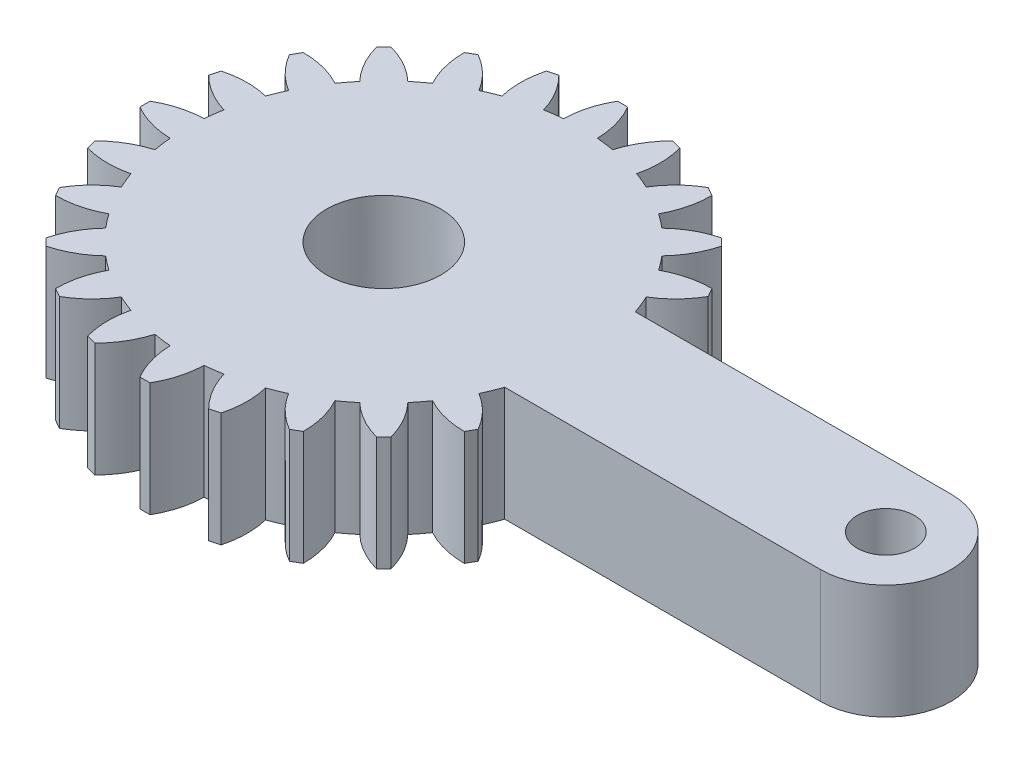
SolidWorks part; units mm, degrees
material "PLA"
ref_plane "Front Plane" through (0, 0, 0) normal (0, 0, 1) x (1, 0, 0)
ref_plane "Top Plane" through (0, 0, 0) normal (0, 1, 0) x (1, 0, 0)
ref_plane "Right Plane" through (0, 0, 0) normal (1, 0, 0) x (0, 0, -1)
sketch "Sketch1" plane through (0, 0, 0) normal (0, 1, 0) x (1, 0, 0)
  line L0 (0, 0) -> (0, 14.63) construction
  line L1 (0, 0) -> (30.75, 0) construction
  line L2 (0.31, 14.63) -> (-0.31, 14.63)
  line L3 (30.75, 4) -> (11.4091, 4)
  line L4 (30.75, -4) -> (11.4091, -4)
  line L5 (4.086, 14.0513) -> (3.4871, 14.2117)
  line L6 (7.5835, 12.515) -> (7.0465, 12.825)
  line L7 (10.5642, 10.1258) -> (10.1258, 10.5642)
  line L8 (12.825, 7.0465) -> (12.515, 7.5835)
  line L9 (14.2117, 3.4871) -> (14.0513, 4.086)
  line L10 (14.63, -0.31) -> (14.63, 0.31)
  line L11 (14.0513, -4.086) -> (14.2117, -3.4871)
  line L12 (12.515, -7.5835) -> (12.825, -7.0465)
  line L13 (10.1258, -10.5642) -> (10.5642, -10.1258)
  line L14 (7.0465, -12.825) -> (7.5835, -12.515)
  line L15 (3.4871, -14.2117) -> (4.086, -14.0513)
  line L16 (-0.31, -14.63) -> (0.31, -14.63)
  line L17 (-4.086, -14.0513) -> (-3.4871, -14.2117)
  line L18 (-7.5835, -12.515) -> (-7.0465, -12.825)
  line L19 (-10.5642, -10.1258) -> (-10.1258, -10.5642)
  line L20 (-12.825, -7.0465) -> (-12.515, -7.5835)
  line L21 (-14.2117, -3.4871) -> (-14.0513, -4.086)
  line L22 (-14.63, 0.31) -> (-14.63, -0.31)
  line L23 (-14.0513, 4.086) -> (-14.2117, 3.4871)
  line L24 (-12.515, 7.5835) -> (-12.825, 7.0465)
  line L25 (-10.1258, 10.5642) -> (-10.5642, 10.1258)
  line L26 (-7.0465, 12.825) -> (-7.5835, 12.515)
  line L27 (-3.4871, 14.2117) -> (-4.086, 14.0513)
  circle A3 centre (0, 0) radius 12.09
  circle A4 centre (0, 0) radius 3.5
  arc A5 (30.75, -4) -> (30.75, 4) centre (30.75, 0) ccw
  arc A6 (-0.31, 14.63) -> (-1.04, 12.0452) centre (4.3585, 11.9161) ccw
  circle A7 centre (30.75, 0) radius 1.75
  arc A8 (0.31, 14.63) -> (1.04, 12.0452) centre (-4.3585, 11.9161) cw
  arc A9 (3.4871, 14.2117) -> (2.113, 11.9039) centre (7.294, 10.382) ccw
  arc A10 (4.086, 14.0513) -> (4.1221, 11.3656) centre (-1.1258, 12.6381) cw
  circle A11 centre (0, 0) radius 12.09
  arc A12 (7.0465, 12.825) -> (5.1219, 10.9514) centre (9.7326, 8.1404) ccw
  arc A13 (7.5835, 12.515) -> (6.9233, 9.9114) centre (2.1835, 12.4988) cw
  circle A14 centre (0, 0) radius 12.09
  arc A15 (10.1258, 10.5642) -> (7.7818, 9.2526) centre (11.5078, 5.344) ccw
  arc A16 (10.5642, 10.1258) -> (9.2526, 7.7818) centre (5.344, 11.5078) cw
  circle A17 centre (0, 0) radius 12.09
  arc A18 (12.515, 7.5835) -> (9.9114, 6.9233) centre (12.4988, 2.1835) ccw
  arc A19 (12.825, 7.0465) -> (10.9514, 5.1219) centre (8.1404, 9.7326) cw
  circle A20 centre (0, 0) radius 12.09
  arc A21 (14.0513, 4.086) -> (11.3656, 4.1221) centre (12.6381, -1.1258) ccw
  arc A22 (14.2117, 3.4871) -> (11.9039, 2.113) centre (10.382, 7.294) cw
  circle A23 centre (0, 0) radius 12.09
  arc A24 (14.63, 0.31) -> (12.0452, 1.04) centre (11.9161, -4.3585) ccw
  arc A25 (14.63, -0.31) -> (12.0452, -1.04) centre (11.9161, 4.3585) cw
  circle A26 centre (0, 0) radius 12.09
  arc A27 (14.2117, -3.4871) -> (11.9039, -2.113) centre (10.382, -7.294) ccw
  arc A28 (14.0513, -4.086) -> (11.3656, -4.1221) centre (12.6381, 1.1258) cw
  circle A29 centre (0, 0) radius 12.09
  arc A30 (12.825, -7.0465) -> (10.9514, -5.1219) centre (8.1404, -9.7326) ccw
  arc A31 (12.515, -7.5835) -> (9.9114, -6.9233) centre (12.4988, -2.1835) cw
  circle A32 centre (0, 0) radius 12.09
  arc A33 (10.5642, -10.1258) -> (9.2526, -7.7818) centre (5.344, -11.5078) ccw
  arc A34 (10.1258, -10.5642) -> (7.7818, -9.2526) centre (11.5078, -5.344) cw
  circle A35 centre (0, 0) radius 12.09
  arc A36 (7.5835, -12.515) -> (6.9233, -9.9114) centre (2.1835, -12.4988) ccw
  arc A37 (7.0465, -12.825) -> (5.1219, -10.9514) centre (9.7326, -8.1404) cw
  circle A38 centre (0, 0) radius 12.09
  arc A39 (4.086, -14.0513) -> (4.1221, -11.3656) centre (-1.1258, -12.6381) ccw
  arc A40 (3.4871, -14.2117) -> (2.113, -11.9039) centre (7.294, -10.382) cw
  circle A41 centre (0, 0) radius 12.09
  arc A42 (0.31, -14.63) -> (1.04, -12.0452) centre (-4.3585, -11.9161) ccw
  arc A43 (-0.31, -14.63) -> (-1.04, -12.0452) centre (4.3585, -11.9161) cw
  circle A44 centre (0, 0) radius 12.09
  arc A45 (-3.4871, -14.2117) -> (-2.113, -11.9039) centre (-7.294, -10.382) ccw
  arc A46 (-4.086, -14.0513) -> (-4.1221, -11.3656) centre (1.1258, -12.6381) cw
  circle A47 centre (0, 0) radius 12.09
  arc A48 (-7.0465, -12.825) -> (-5.1219, -10.9514) centre (-9.7326, -8.1404) ccw
  arc A49 (-7.5835, -12.515) -> (-6.9233, -9.9114) centre (-2.1835, -12.4988) cw
  circle A50 centre (0, 0) radius 12.09
  arc A51 (-10.1258, -10.5642) -> (-7.7818, -9.2526) centre (-11.5078, -5.344) ccw
  arc A52 (-10.5642, -10.1258) -> (-9.2526, -7.7818) centre (-5.344, -11.5078) cw
  circle A53 centre (0, 0) radius 12.09
  arc A54 (-12.515, -7.5835) -> (-9.9114, -6.9233) centre (-12.4988, -2.1835) ccw
  arc A55 (-12.825, -7.0465) -> (-10.9514, -5.1219) centre (-8.1404, -9.7326) cw
  circle A56 centre (0, 0) radius 12.09
  arc A57 (-14.0513, -4.086) -> (-11.3656, -4.1221) centre (-12.6381, 1.1258) ccw
  arc A58 (-14.2117, -3.4871) -> (-11.9039, -2.113) centre (-10.382, -7.294) cw
  circle A59 centre (0, 0) radius 12.09
  arc A60 (-14.63, -0.31) -> (-12.0452, -1.04) centre (-11.9161, 4.3585) ccw
  arc A61 (-14.63, 0.31) -> (-12.0452, 1.04) centre (-11.9161, -4.3585) cw
  circle A62 centre (0, 0) radius 12.09
  arc A63 (-14.2117, 3.4871) -> (-11.9039, 2.113) centre (-10.382, 7.294) ccw
  arc A64 (-14.0513, 4.086) -> (-11.3656, 4.1221) centre (-12.6381, -1.1258) cw
  circle A65 centre (0, 0) radius 12.09
  arc A66 (-12.825, 7.0465) -> (-10.9514, 5.1219) centre (-8.1404, 9.7326) ccw
  arc A67 (-12.515, 7.5835) -> (-9.9114, 6.9233) centre (-12.4988, 2.1835) cw
  circle A68 centre (0, 0) radius 12.09
  arc A69 (-10.5642, 10.1258) -> (-9.2526, 7.7818) centre (-5.344, 11.5078) ccw
  arc A70 (-10.1258, 10.5642) -> (-7.7818, 9.2526) centre (-11.5078, 5.344) cw
  circle A71 centre (0, 0) radius 12.09
  arc A72 (-7.5835, 12.515) -> (-6.9233, 9.9114) centre (-2.1835, 12.4988) ccw
  arc A73 (-7.0465, 12.825) -> (-5.1219, 10.9514) centre (-9.7326, 8.1404) cw
  circle A74 centre (0, 0) radius 12.09
  arc A75 (-4.086, 14.0513) -> (-4.1221, 11.3656) centre (1.1258, 12.6381) ccw
  arc A76 (-3.4871, 14.2117) -> (-2.113, 11.9039) centre (-7.294, 10.382) cw
  circle A77 centre (0, 0) radius 12.09
  point P181 (0, 0)
  dimension "D2" = 7
  dimension "D3" = 0.31
  dimension "D4" = 1.04
  dimension "D7" = 30.75
  dimension "D1" = 24.18
  dimension "D5" = 5.4
  dimension "D8" = 8
  dimension "D9" = 3.5
  dimension "D6" = 14.63
  dimension "D10" = 24
extrude "Boss-Extrude1" add sketch "Sketch1" along normal blind 7 contours A8 L2 A6 A3 | A10 L5 A9 A3 | A76 L27 A75 A74 | A73 L26 A72 A71 | A70 L25 A69 A68 | A67 L24 A66 A65 | A64 L23 A63 A62 | A61 L22 A60 A59 | A58 L21 A57 A56 | A55 L20 A54 A53 | A49 L18 A48 A47 | A46 L17 A45 A44 | A52 L19 A51 A50 | A43 L16 A42 A41 | A40 L15 A39 A38 | A37 L14 A36 A35 | A34 L13 A33 A32 | A31 L12 A30 A29 | L11 A27 A3 L4 | A25 L10 A24 A23 | A22 L9 L3 A20 | A27 L11 L4 A5 L3 L9 A22 A23 A24 L10 A25 A26 A7 | A19 L8 A18 A17 | A16 L7 A15 A14 | A13 L6 A12 A11 | A3 A20 A17 A14 A11 A74 A71 A68 A65 A62 A59 A56 A53 A50 A47 A44 A41 A38 A35 A32 A29 A26 A23 | A4
sketch "Sketch2" plane through (0, 0, 0) normal (0, -1, 0) x (1, 0, 0)
  circle A0 centre (0, 0) radius 3.5
  circle A1 centre (0, 0) radius 1.75
  dimension "D1" = 7
  dimension "D2" = 3.5
extrude "Boss-Extrude2" add sketch "Sketch2" against normal blind 2
